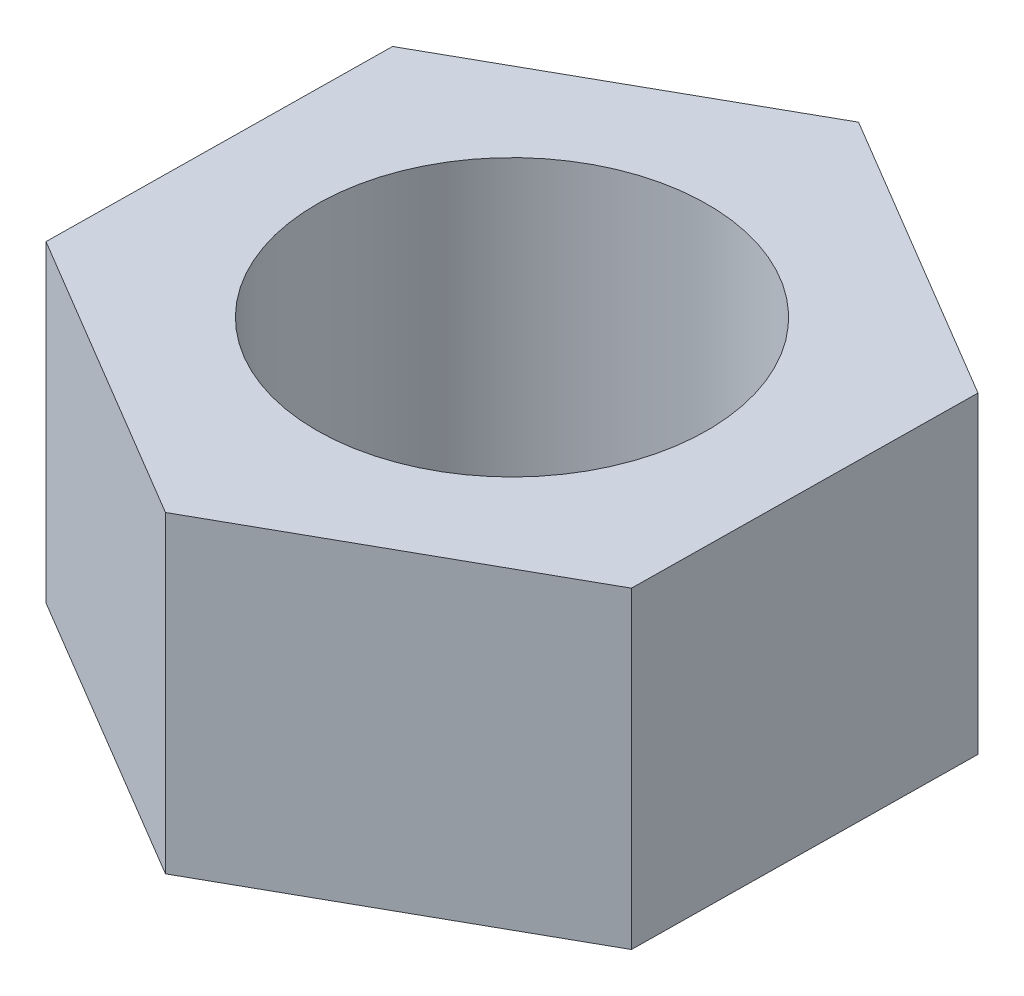
SolidWorks part; units mm, degrees
ref_plane "Front Plane" through (0, 0, 0) normal (0, 0, 1) x (1, 0, 0)
ref_plane "Top Plane" through (0, 0, 0) normal (0, 1, 0) x (1, 0, 0)
ref_plane "Right Plane" through (0, 0, 0) normal (1, 0, 0) x (0, 0, -1)
sketch "Sketch2" plane through (0, 0, 0) normal (0, 1, 0) x (1, 0, 0)
  line L0 (-3.0527, -1.7121) -> (3.0527, 1.7121) construction
  line L1 (3.009, -1.7877) -> (3.0527, 1.7121)
  line L2 (3.0527, 1.7121) -> (0.0436, 3.4997)
  line L3 (0.0436, 3.4997) -> (-3.009, 1.7877)
  line L4 (-3.009, 1.7877) -> (-3.0527, -1.7121)
  line L5 (-3.0527, -1.7121) -> (-0.0436, -3.4997)
  line L6 (-0.0436, -3.4997) -> (3.009, -1.7877)
  circle A0 centre (0, 0) radius 3.0311 construction
  circle A1 centre (0, 0) radius 2
  dimension "D2" = 4
  dimension "D1" = 7
extrude "Boss-Extrude1" add sketch "Sketch2" along normal blind 3.2
